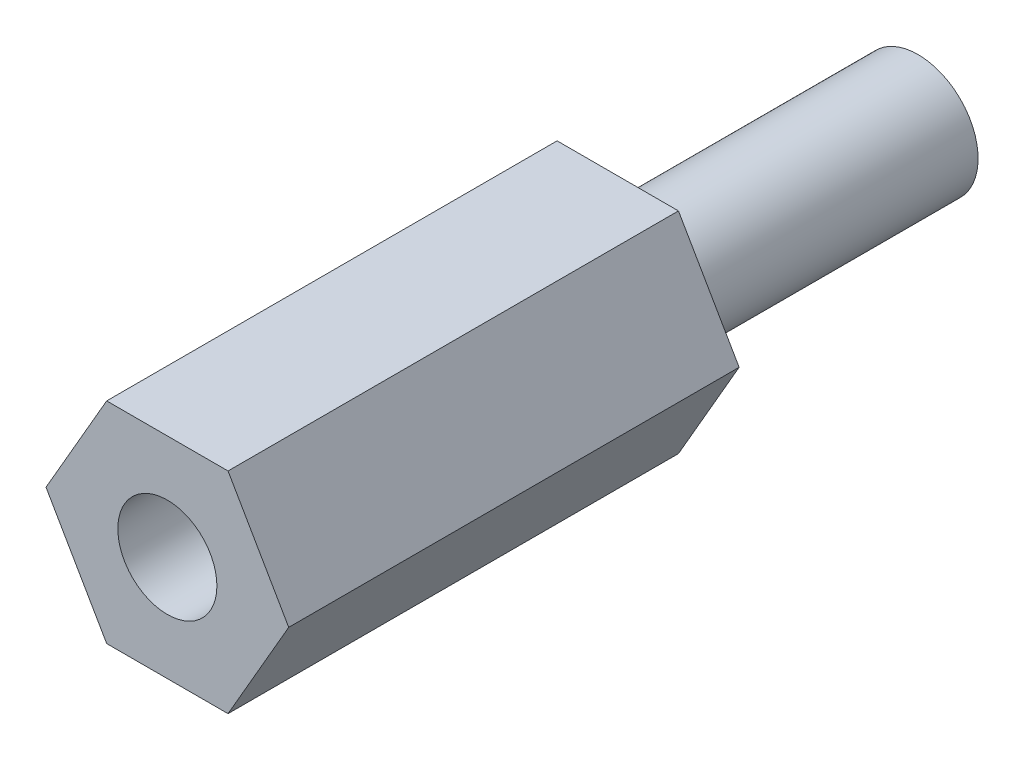
SolidWorks part; units mm, degrees
material "黃銅"
ref_plane "前基準面" through (0, 0, 0) normal (0, 0, 1) x (1, 0, 0)
ref_plane "上基準面" through (0, 0, 0) normal (0, 1, 0) x (1, 0, 0)
ref_plane "右基準面" through (0, 0, 0) normal (1, 0, 0) x (0, 0, -1)
sketch "草圖1" plane through (0, 0, 0) normal (0, 0, 1) x (1, 0, 0)
  line L1 (-2.0207, 3.5) -> (-4.0415, 0)
  line L2 (-4.0415, 0) -> (-2.0207, -3.5)
  line L3 (-2.0207, -3.5) -> (2.0207, -3.5)
  line L4 (2.0207, -3.5) -> (4.0415, 0)
  line L5 (4.0415, 0) -> (2.0207, 3.5)
  line L6 (2.0207, 3.5) -> (-2.0207, 3.5)
  circle A0 centre (0, 0) radius 3.5 construction
  dimension "D1" = 7
extrude "填料-伸長1" add sketch "草圖1" along normal blind 15
sketch "草圖4" plane through (0, 0, 0) normal (0, 0, -1) x (-1, 0, 0)
  circle A0 centre (0, 0) radius 2
  dimension "D1" = 4
extrude "填料-伸長2" add sketch "草圖4" along normal blind 10
hole_wizard "M4x0.7 螺紋孔1" positions "草圖2" profile "草圖3" tap size "M4x0.7" standard "Ansi Metric"
sketch "草圖2" plane through (0, 0, 15) normal (0, 0, 1) x (1, 0, 0)
  point P0 (0, 0)
sketch "草圖3" plane through (0, 0, 15) normal (1, 0, 0) x (0, -1, 0)
  line L0 (0, 0) -> (0, 11.0914)
  line L1 (0, 11.0914) -> (1.65, 10.1)
  line L2 (1.65, 10.1) -> (1.65, 0)
  line L5 (1.65, 0) -> (0, 0)
  line L10 (0, 11.0914) -> (-1.65, 10.1) construction
  line L11 (0, -6.35) -> (0, 107.95) construction
  dimension "螺孔鑽直徑" = 3.3
  dimension "螺孔鑽深度" = 10.1
  dimension "導頭角度" = 118
